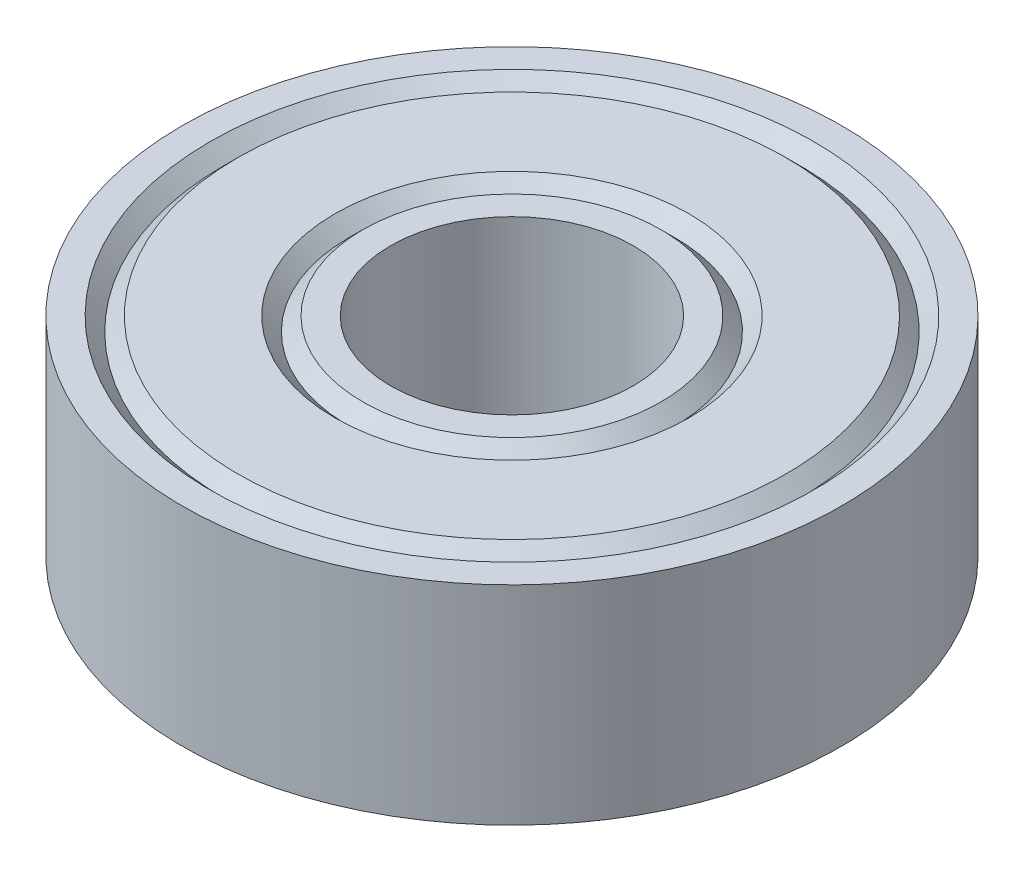
SolidWorks part; units mm, degrees
ref_plane "Front Plane" through (0, 0, 0) normal (0, 0, 1) x (1, 0, 0)
ref_plane "Top Plane" through (0, 0, 0) normal (0, 1, 0) x (1, 0, 0)
ref_plane "Right Plane" through (0, 0, 0) normal (1, 0, 0) x (0, 0, -1)
sketch "Sketch1" plane through (0, 0, 0) normal (0, 0, 1) x (1, 0, 0)
  line L0 (0, 3) -> (0, -3) construction
  line L1 (-3.5, 3) -> (-4.3, 3)
  line L2 (-3.5, 3) -> (-3.5, -3)
  line L3 (-3.5, -3) -> (-4.3, -3)
  line L4 (-9.5, 3) -> (-9.5, -3)
  line L5 (-8.7, 3) -> (-8.3, 2.6)
  line L6 (-8.3, 2.6) -> (-7.9, 3)
  line L7 (-5.1, 3) -> (-4.7, 2.6)
  line L8 (-4.7, 2.6) -> (-4.3, 3)
  line L9 (-8.7, -3) -> (-8.3, -2.6)
  line L10 (-8.3, -2.6) -> (-7.9, -3)
  line L11 (-5.1, -3) -> (-4.7, -2.6)
  line L12 (-4.7, -2.6) -> (-4.3, -3)
  line L13 (-5.1, -3) -> (-7.9, -3)
  line L14 (-8.7, -3) -> (-9.5, -3)
  line L15 (-8.7, 3) -> (-9.5, 3)
  line L16 (-5.1, 3) -> (-7.9, 3)
  line L17 (-8.3, 2.6) -> (-4.7, 2.6) construction
  line L18 (-8.3, 2.6) -> (-8.3, -2.6) construction
  line L19 (-4.7, -2.6) -> (-8.3, -2.6) construction
  line L20 (-4.7, 2.6) -> (-4.7, -2.6) construction
  line L21 (-8.3, 0) -> (-7.1, 0) construction
  line L22 (-4.3, 3) -> (-5.1, 3) construction
  line L23 (-7.1, 0) -> (-5.9, 0) construction
  line L24 (-8.3, 0) -> (-9.5, 0) construction
  line L25 (-5.9, 0) -> (-4.7, 0) construction
  line L26 (-4.7, 0) -> (-3.5, 0) construction
  dimension "D1" = 6
  dimension "D2" = 7
  dimension "D3" = 19
revolve "Revolve1" add sketch "Sketch1" angle 360 about L0
